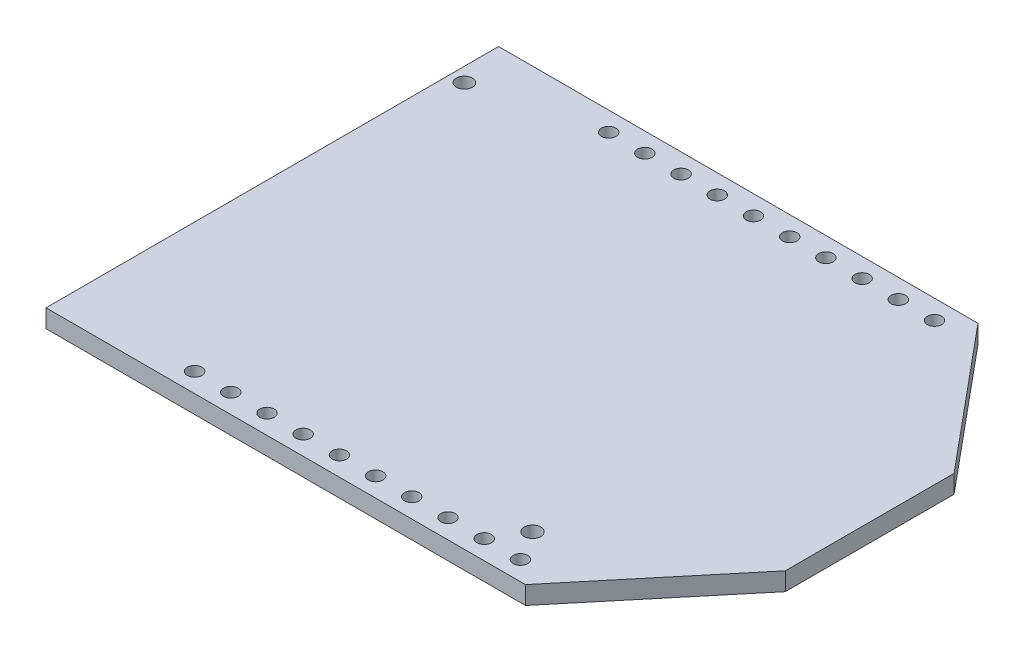
SolidWorks part; units mm, degrees
ref_plane "Front Plane" through (0, 0, 0) normal (0, 0, 1) x (1, 0, 0)
ref_plane "Top Plane" through (0, 0, 0) normal (0, 1, 0) x (1, 0, 0)
ref_plane "Right Plane" through (0, 0, 0) normal (1, 0, 0) x (0, 0, -1)
sketch "Sketch1" plane through (0, 0, 0) normal (0, 1, 0) x (1, 0, 0)
  line L1 (0, 0) -> (33, 0)
  line L2 (0, 0) -> (0, 25)
  line L3 (0, 25) -> (33, 25)
  line L4 (33, 0) -> (33, 25)
  dimension "D1" = 33
  dimension "D2" = 25
extrude "Boss-Extrude1" add sketch "Sketch1" along normal blind 1
sketch "Sketch2" plane through (0, 0, 0) normal (0, -1, 0) x (1, 0, 0)
  line L0 (33, -12.5) -> (0, -12.5) construction
  line L1 (33, 0) -> (33, -25) construction
  line L2 (0, -25) -> (0, 0) construction
  line L3 (33, 0) -> (26.483, 0)
  line L4 (0, 0) -> (33, 0) construction
  line L5 (26.483, 0) -> (33, -7.8378)
  line L6 (33, -7.8378) -> (33, 0)
  line L7 (33, -17.1622) -> (33, -25)
  line L8 (26.483, -25) -> (33, -17.1622)
  line L9 (33, -25) -> (26.483, -25)
extrude "Cut-Extrude1" cut sketch "Sketch2" against normal through all
sketch "Sketch3" plane through (0, 1, 0) normal (0, 1, 0) x (1, 0, 0)
  circle A0 centre (7.1439, 23.9361) radius 0.4
  circle A1 centre (9.1439, 23.9361) radius 0.4
  circle A2 centre (11.1439, 23.9361) radius 0.4
  circle A3 centre (13.1439, 23.9361) radius 0.4
  circle A4 centre (15.1439, 23.9361) radius 0.4
  circle A5 centre (17.1439, 23.9361) radius 0.4
  circle A6 centre (19.1439, 23.9361) radius 0.4
  circle A7 centre (21.1439, 23.9361) radius 0.4
  circle A8 centre (23.1439, 23.9361) radius 0.4
  circle A9 centre (25.1439, 23.9361) radius 0.4
  circle A10 centre (25.1439, 1.0639) radius 0.4
  circle A11 centre (23.1439, 1.0639) radius 0.4
  circle A12 centre (21.1439, 1.0639) radius 0.4
  circle A13 centre (19.1439, 1.0639) radius 0.4
  circle A14 centre (17.1439, 1.0639) radius 0.4
  circle A15 centre (15.1439, 1.0639) radius 0.4
  circle A16 centre (13.1439, 1.0639) radius 0.4
  circle A17 centre (11.1439, 1.0639) radius 0.4
  circle A18 centre (9.1439, 1.0639) radius 0.4
  circle A19 centre (7.1439, 1.0639) radius 0.4
  circle A20 centre (0.7843, 22.3251) radius 0.4421
  circle A22 centre (24.1527, 2.7223) radius 0.4582
  dimension "D1" = 0.8
  dimension "D2" = 10
extrude "Cut-Extrude2" cut sketch "Sketch3" against normal through all
sketch "Sketch4" plane through (0, 1, 0) normal (0, 1, 0) x (1, 0, 0)
  line L0 (0, 0) -> (26.483, 0) construction
  circle A0 centre (26.2119, 8) radius 0.75
  dimension "D1" = 1.5
  dimension "D2" = 8
ref_plane "Plane1" through (0, 0, -8) normal (0, 0, 1) x (1, 0, 0)
sketch "Sketch6" plane through (0, 0, 0) normal (0, -1, 0) x (1, 0, 0)
  line L1 (24.5079, -22.429) -> (0.7782, -22.429)
  line L2 (25.0079, -21.929) -> (25.0079, -2.9033)
  line L3 (24.5079, -2.4033) -> (0.7782, -2.4033)
  line L4 (0.2782, -21.929) -> (0.2782, -2.9033)
  arc A0 (0.7782, -2.4033) -> (0.2782, -2.9033) centre (0.7782, -2.9033) ccw
  arc A1 (0.7782, -22.429) -> (0.2782, -21.929) centre (0.7782, -21.929) cw
  arc A2 (24.5079, -22.429) -> (25.0079, -21.929) centre (24.5079, -21.929) ccw
  arc A3 (25.0079, -2.9033) -> (24.5079, -2.4033) centre (24.5079, -2.9033) ccw
  dimension "D1" = 0.5
  dimension "D2" = 0.5
extrude "Boss-Extrude3" add sketch "Sketch6" along normal blind 2
